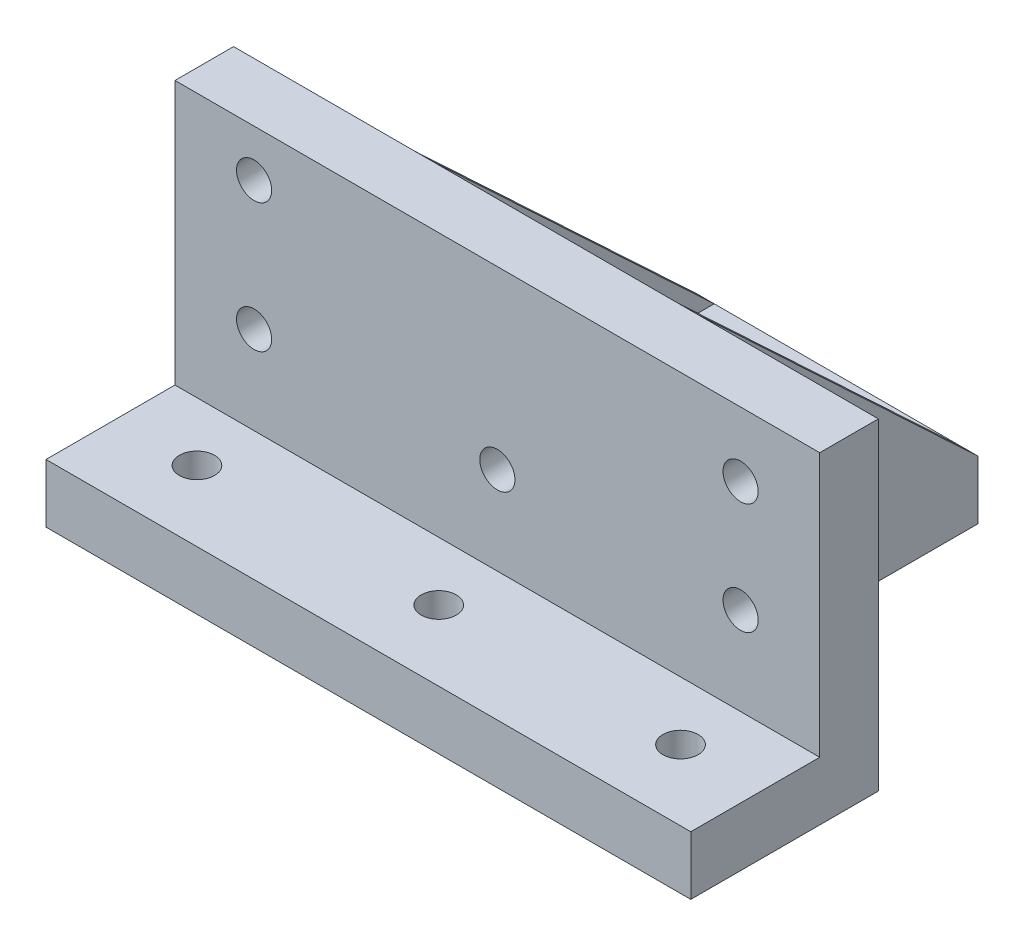
SolidWorks part; units mm, degrees
ref_plane "Спереди" through (0, 0, 0) normal (0, 0, 1) x (1, 0, 0)
ref_plane "Сверху" through (0, 0, 0) normal (0, 1, 0) x (1, 0, 0)
ref_plane "Справа" through (0, 0, 0) normal (1, 0, 0) x (0, 0, -1)
sketch "Эскиз1" plane through (0, 0, 0) normal (0, 1, 0) x (1, 0, 0)
  line L0 (0, 0) -> (-16, 0) construction
  line L1 (0, 0) -> (0, 16) construction
  line L2 (0, -24) -> (0, -56) construction
  line L3 (-24, 24) -> (24, 24)
  line L4 (-24, 24) -> (-24, -24)
  line L6 (24, 24) -> (24, -24)
  line L7 (-24, 24) -> (24, -24) construction
  line L8 (-24, -24) -> (24, 24) construction
  line L9 (0, -56) -> (-55, -56) construction
  line L10 (0, -56) -> (55, -56) construction
  line L11 (24, -24) -> (55, -24)
  line L12 (-55, -56) -> (55, -56)
  line L13 (-55, -56) -> (-55, -24)
  line L14 (-55, -24) -> (-24, -24)
  line L15 (55, -56) -> (55, -24)
  circle A0 centre (0, 0) radius 12
  circle A1 centre (-16, 16) radius 1.75
  circle A2 centre (16, 16) radius 1.75
  circle A3 centre (16, -16) radius 1.75
  circle A4 centre (-16, -16) radius 1.75
  dimension "D1" = 24
  dimension "D4" = 3.5
  dimension "D2" = 16
  dimension "D3" = 16
  dimension "D7" = 48
  dimension "D8" = 32
  dimension "D9" = 55
  dimension "D10" = 55
  dimension "D5" = 2
  dimension "D6" = 2
extrude "Бобышка-Вытянуть1" add sketch "Эскиз1" along normal blind 10
sketch "Эскиз2" plane through (0, 10, 0) normal (0, 1, 0) x (1, 0, 0)
  line L0 (55, -56) -> (55, -24) construction
  line L1 (-55, -24) -> (55, -24)
  line L2 (-55, -24) -> (-55, -34)
  line L3 (-55, -34) -> (55, -34)
  line L4 (55, -24) -> (55, -34)
  dimension "D1" = 10
extrude "Бобышка-Вытянуть2" add sketch "Эскиз2" along normal blind 45
sketch "Эскиз5" plane through (0, 10, 0) normal (0, 1, 0) x (1, 0, 0)
  line L0 (-55, -66.2734) -> (55, -66.2734) construction
  line L1 (-55, -71.1392) -> (0, -71.1392) construction
  line L2 (-55, -80.1997) -> (-27.5, -80.1997) construction
  line L3 (55, -80.1997) -> (27.5, -80.1997) construction
  line L4 (-58.0091, -56) -> (-58.0091, -34) construction
  line L5 (-60.3127, -34) -> (-60.3127, -54) construction
  circle A0 centre (-41.25, -44) radius 3
  circle A1 centre (0, -44) radius 3
  circle A2 centre (41.25, -44) radius 3
  dimension "D1" = 6
  dimension "D2" = 6
  dimension "D4" = 6
  dimension "D3" = 27.5
  dimension "D5" = 20
extrude "Вырез-Вытянуть2" cut sketch "Эскиз5" against normal through all
sketch "Эскиз6" plane through (0, 0, 0) normal (0, -1, 0) x (1, 0, 0)
  circle A0 centre (-41.25, 44) radius 5
  circle A1 centre (0, 44) radius 5
  circle A2 centre (41.25, 44) radius 5
  dimension "D1" = 10
  dimension "D2" = 10
  dimension "D3" = 10
extrude "Вырез-Вытянуть3" cut sketch "Эскиз6" against normal blind 5
sketch "Эскиз7" plane through (0, 0, 34) normal (0, 0, 1) x (1, 0, 0)
  line L0 (-59.6742, 15) -> (-59.6742, 38) construction
  line L1 (-69.9041, 15) -> (-69.9041, 35) construction
  line L2 (-55, 47.894) -> (-28, 47.894) construction
  line L3 (55, 47.894) -> (28, 47.894) construction
  circle A0 centre (-41.5, 25) radius 3
  circle A1 centre (41.5, 25) radius 3
  circle A2 centre (0, 25) radius 3
  dimension "D4" = 6
  dimension "D5" = 6
  dimension "D6" = 6
  dimension "D1" = 20
  dimension "D2" = 27
  dimension "D3" = 27
extrude "Вырез-Вытянуть4" cut sketch "Эскиз7" against normal through all
sketch "Эскиз8" plane through (0, 0, 24) normal (0, 0, -1) x (-1, 0, 0)
  circle A0 centre (-41.5, 25) radius 5
  circle A1 centre (0, 25) radius 5
  circle A2 centre (41.5, 25) radius 5
  dimension "D1" = 10
  dimension "D2" = 10
  dimension "D3" = 10
extrude "Вырез-Вытянуть5" cut sketch "Эскиз8" against normal blind 5
sketch "Эскиз10" plane through (24, 0, 0) normal (1, 0, 0) x (0, 0, -1)
  line L0 (-24, 10) -> (-24, 55)
  line L1 (-24, 55) -> (24, 10)
  line L2 (24, 10) -> (-24, 10)
extrude "Бобышка-Вытянуть3" add sketch "Эскиз10" against normal blind 3
sketch "Эскиз11" plane through (-24, 0, 0) normal (-1, 0, 0) x (0, 0, 1)
  line L0 (24, 10) -> (-24, 10)
  line L1 (-24, 10) -> (24, 55)
  line L2 (24, 55) -> (24, 10)
extrude "Бобышка-Вытянуть4" add sketch "Эскиз11" against normal blind 3
sketch "Эскиз14" plane through (0, 0, 34) normal (0, 0, 1) x (1, 0, 0)
  circle A0 centre (-41.5, 47.0048) radius 3
  circle A1 centre (41.5, 44.0048) radius 3
  dimension "D1" = 6
  dimension "D2" = 6
extrude "Вырез-Вытянуть9" cut sketch "Эскиз14" against normal through all
sketch "Эскиз15" plane through (0, 0, 24) normal (0, 0, -1) x (-1, 0, 0)
  circle A0 centre (41.5, 47.0048) radius 5
  circle A1 centre (-41.5, 44.0048) radius 5
  dimension "D1" = 10
  dimension "D2" = 10
extrude "Вырез-Вытянуть10" cut sketch "Эскиз15" against normal blind 5
sketch "Эскиз16" plane through (0, 10, 0) normal (0, 1, 0) x (1, 0, 0)
  circle A0 centre (16, 16) radius 3
  circle A1 centre (16, -16) radius 3
  circle A2 centre (-16, 16) radius 3
  circle A3 centre (-16, -16) radius 3
  dimension "D1" = 6
  dimension "D2" = 6
  dimension "D3" = 6
  dimension "D4" = 6
extrude "Вырез-Вытянуть11" cut sketch "Эскиз16" against normal blind 5
